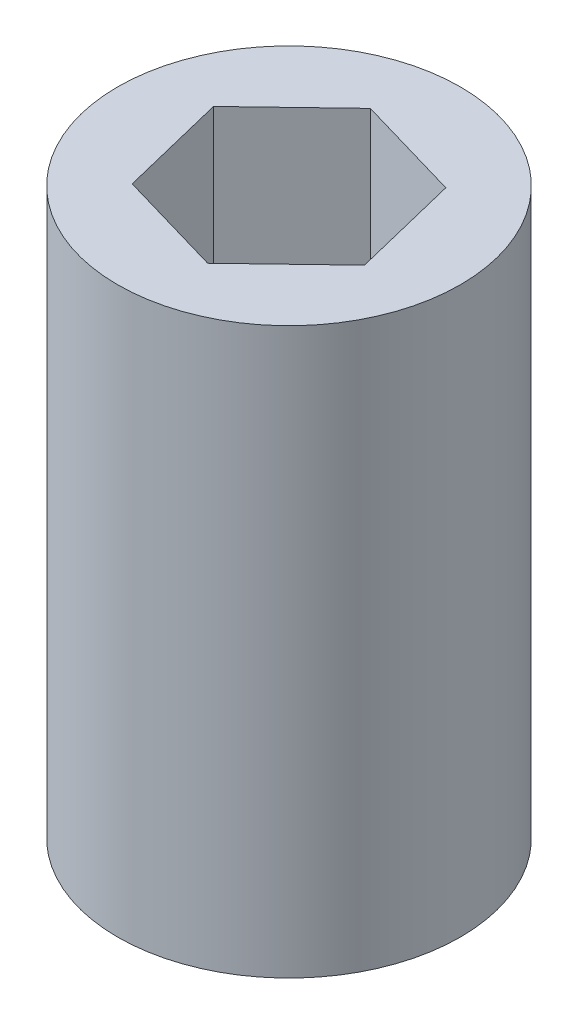
SolidWorks part; units mm, degrees
ref_plane "Front" through (0, 0, 0) normal (0, 0, 1) x (1, 0, 0)
ref_plane "Top" through (0, 0, 0) normal (0, 1, 0) x (1, 0, 0)
ref_plane "Right" through (0, 0, 0) normal (1, 0, 0) x (0, 0, -1)
sketch "Sketch1" plane through (0, 0, 0) normal (0, 1, 0) x (1, 0, 0)
  circle A0 centre (0, 0) radius 4.55
extrude "Boss-Extrude1" add sketch "Sketch1" along normal blind 15
sketch "Sketch2" plane through (0, 15, 0) normal (0, 1, 0) x (1, 0, 0)
  line L1 (-2.1264, -2.0368) -> (0.7008, -2.8599)
  line L2 (0.7008, -2.8599) -> (2.8271, -0.8231)
  line L3 (2.8271, -0.8231) -> (2.1264, 2.0368)
  line L4 (2.1264, 2.0368) -> (-0.7008, 2.8599)
  line L5 (-0.7008, 2.8599) -> (-2.8271, 0.8231)
  line L6 (-2.8271, 0.8231) -> (-2.1264, -2.0368)
  circle A0 centre (0, 0) radius 2.55 construction
  dimension "D1" = 5.1
extrude "Cut-Extrude1" cut sketch "Sketch2" against normal blind 15
